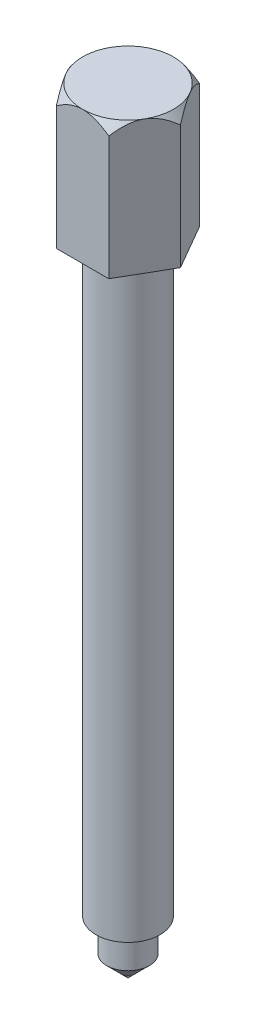
SolidWorks part; units mm, degrees
ref_plane "Front Plane" through (0, 0, 0) normal (0, 0, 1) x (1, 0, 0)
ref_plane "Top Plane" through (0, 0, 0) normal (0, 1, 0) x (1, 0, 0)
ref_plane "Right Plane" through (0, 0, 0) normal (1, 0, 0) x (0, 0, -1)
sketch "Sketch1" plane through (0, 0, 0) normal (0, 1, 0) x (1, 0, 0)
  line L1 (9.815, 0) -> (4.9075, 8.5)
  line L2 (4.9075, 8.5) -> (-4.9075, 8.5)
  line L3 (-4.9075, 8.5) -> (-9.815, 0)
  line L4 (-9.815, 0) -> (-4.9075, -8.5)
  line L5 (-4.9075, -8.5) -> (4.9075, -8.5)
  line L6 (4.9075, -8.5) -> (9.815, 0)
  circle A0 centre (0, 0) radius 8.5 construction
  dimension "D1" = 17
extrude "Boss-Extrude1" add sketch "Sketch1" against normal blind 25
sketch "Sketch2" plane through (0, 0, 0) normal (0, 1, 0) x (1, 0, 0)
  circle A0 centre (0, 0) radius 8.5
extrude "Cut-Extrude1" cut sketch "Sketch2" against normal blind 25 draft 35 flip side to cut
sketch "Sketch3" plane through (0, -25, 0) normal (0, -1, 0) x (1, 0, 0)
  circle A0 centre (0, 0) radius 6
  dimension "D1" = 12
extrude "Boss-Extrude2" add sketch "Sketch3" along normal blind 110
sketch "Sketch4" plane through (0, -135, 0) normal (0, -1, 0) x (1, 0, 0)
  circle A0 centre (0, 0) radius 4
  dimension "D1" = 8
extrude "Boss-Extrude3" add sketch "Sketch4" along normal blind 6
sketch "Sketch6" plane through (0, -141, 0) normal (0, -1, 0) x (1, 0, 0)
  circle A0 centre (0, 0) radius 4
extrude "Boss-Extrude4" add sketch "Sketch6" along normal blind 6 draft 45
